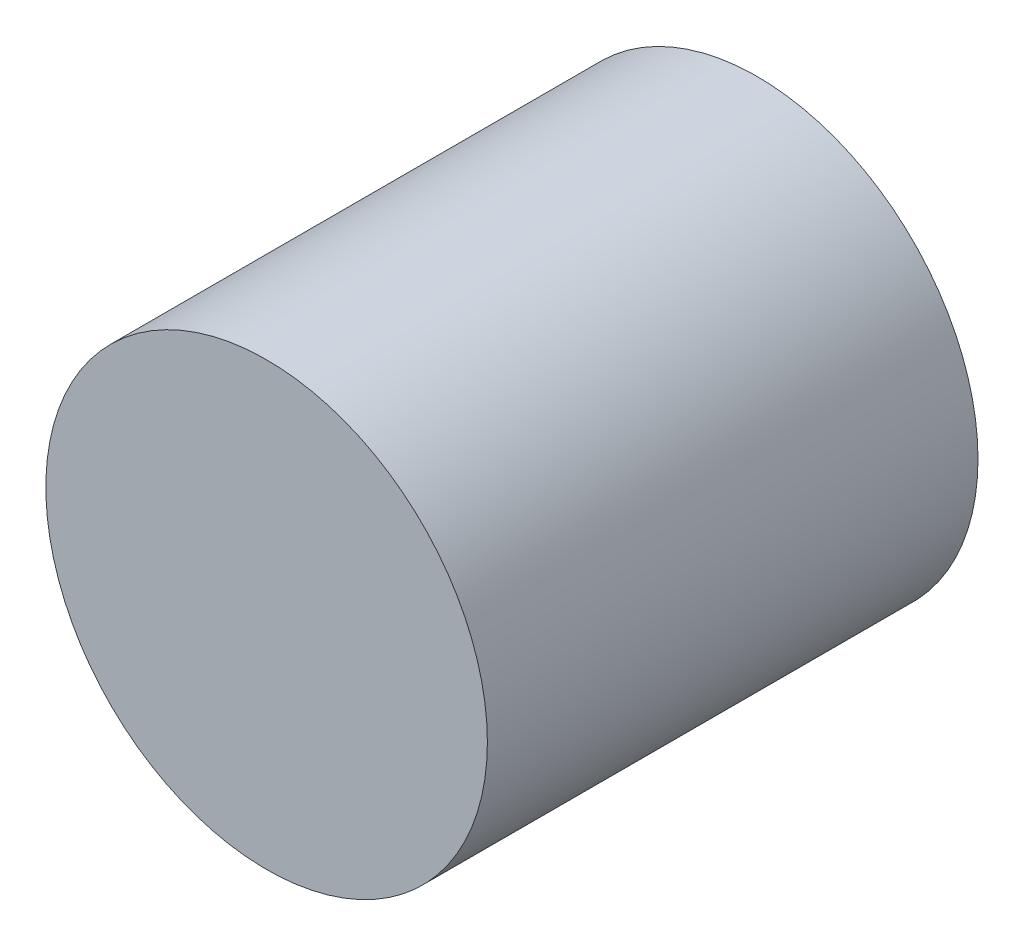
SolidWorks part; units mm, degrees
ref_plane "Piano frontale" through (0, 0, 0) normal (0, 0, 1) x (1, 0, 0)
ref_plane "Piano superiore" through (0, 0, 0) normal (0, 1, 0) x (1, 0, 0)
ref_plane "Piano destro" through (0, 0, 0) normal (1, 0, 0) x (0, 0, -1)
sketch "Schizzo1" plane through (0, 0, 0) normal (0, 0, 1) x (1, 0, 0)
  circle A0 centre (0, 0) radius 54
  dimension "D1" = 108
extrude "Estrusione-Estrusione1" add sketch "Schizzo1" along normal blind 120
